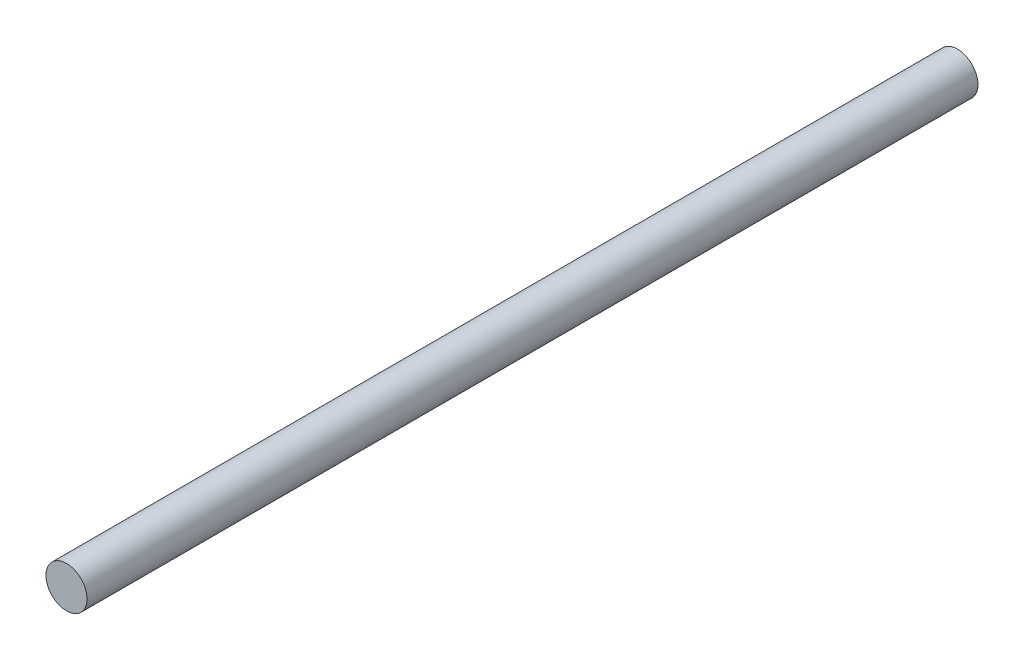
SolidWorks part; units mm, degrees
ref_plane "Front Plane" through (0, 0, 0) normal (0, 0, 1) x (1, 0, 0)
ref_plane "Top Plane" through (0, 0, 0) normal (0, 1, 0) x (1, 0, 0)
ref_plane "Right Plane" through (0, 0, 0) normal (1, 0, 0) x (0, 0, -1)
sketch "Sketch1" plane through (0, 0, 0) normal (0, 0, 1) x (1, 0, 0)
  circle A0 centre (0, 0) radius 3
  dimension "D1" = 6
extrude "Boss-Extrude1" add sketch "Sketch1" along normal blind 130
